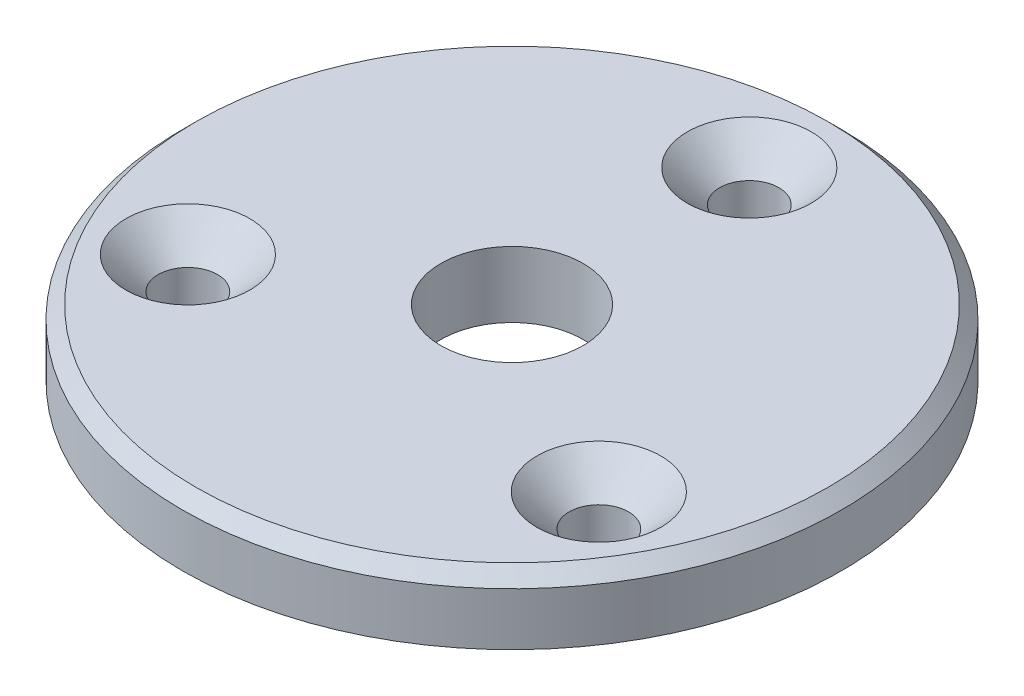
SolidWorks part; units mm, degrees
ref_plane "Front Plane" through (0, 0, 0) normal (0, 0, 1) x (1, 0, 0)
ref_plane "Top Plane" through (0, 0, 0) normal (0, 1, 0) x (1, 0, 0)
ref_plane "Right Plane" through (0, 0, 0) normal (1, 0, 0) x (0, 0, -1)
sketch "Sketch1" plane through (0, 0, 0) normal (0, 1, 0) x (1, 0, 0)
  circle A1 centre (0, 0) radius 25
  dimension "D1" = 50
extrude "Boss-Extrude1" add sketch "Sketch1" along normal blind 5
chamfer "Chamfer1" distance 1 angle 45 1 edges at (0, 5, 25)
sketch "Sketch2" plane through (0, 5, 0) normal (0, 1, 0) x (1, 0, 0)
  line L0 (0, 5.75) -> (0, 24) construction
  circle A2 centre (0, 0) radius 5.75
  circle A3 centre (0, 0) radius 24 construction
  point P7 (0, 18)
  dimension "D1" = 11.5
  dimension "D2" = 6
hole_wizard "CSK for M4 Countersunk Flat Head1" positions "3DSketch1" profile "Sketch3" countersink size "M4" standard "BSI" end condition through all
sketch3d "3DSketch1"
  point P0 (0, 5, -18)
sketch "Sketch3" plane through (0, 5, -18) normal (1, 0, 0) x (0, 0, 1)
  line L0 (0, 0) -> (0, 5)
  line L1 (0, 5) -> (2.25, 5)
  line L2 (2.25, 5) -> (2.25, 2.45)
  line L3 (2.25, 2.45) -> (4.7, 0)
  line L5 (4.7, 0) -> (0, 0)
  line L6 (-2.25, 2.45) -> (-4.7, 0) construction
  line L11 (0, -6.35) -> (0, 107.95) construction
  dimension "Thru Hole Dia." = 4.5
  dimension "Thru Hole Depth" = 5
  dimension "Near C'Sink Dia." = 9.4
  dimension "Near C'Sink Angle" = 90
hole_wizard "M12x1.25 Tapped Hole1" positions "3DSketch2" profile "Sketch4" tap size "M12x1.25" standard "BSI" end condition through all
sketch3d "3DSketch2"
  point P0 (0, 0, 0)
  point P3 (0, 5, 0)
cosmetic thread "Hole Thread1" parameters "D2"=12
cosmetic thread "Hole Thread2" parameters "D2"=12
sketch "Sketch4" plane through (0, 5, 0) normal (1, 0, 0) x (0, 0, 1)
  line L0 (0, 0) -> (0, 5)
  line L1 (0, 5) -> (5.4, 5)
  line L2 (5.4, 5) -> (5.4, 0)
  line L5 (5.4, 0) -> (0, 0)
  line L11 (0, -6.35) -> (0, 107.95) construction
  dimension "Thru Tap Drill Dia." = 10.8
  dimension "Thru Tap Drill Depth" = 5
pattern_circular "CirPattern1" count 3 over 360 about axis through (0, 0, 0) along (0, 1, 0) of "CSK for M4 Countersunk Flat Head1"
